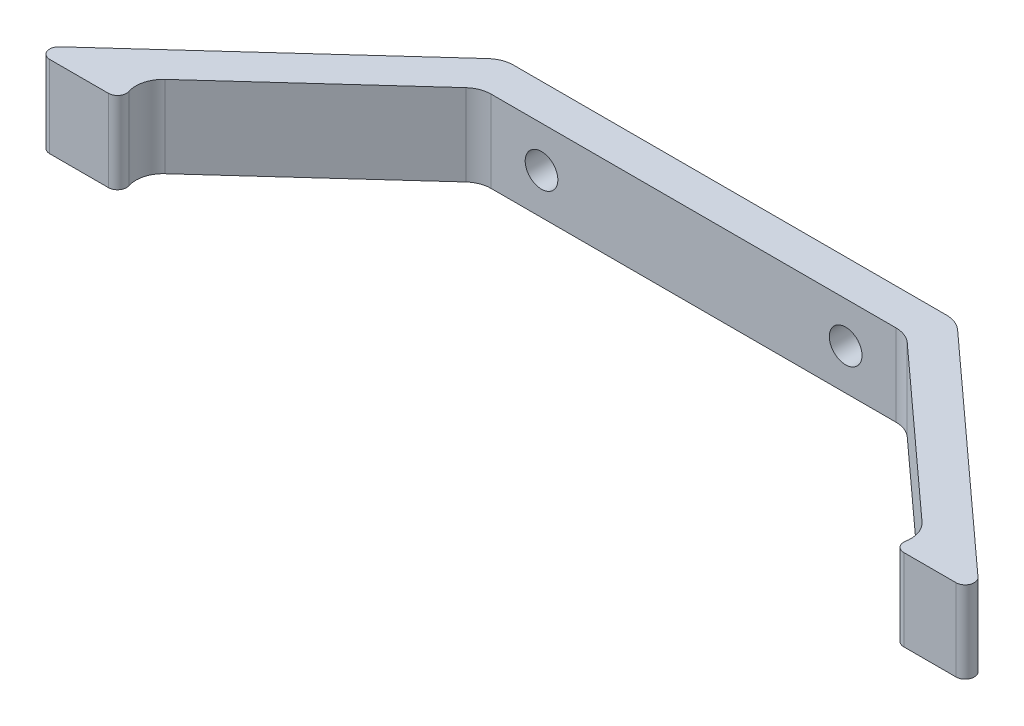
SolidWorks part; units mm, degrees
ref_plane "Front Plane" through (0, 0, 0) normal (0, 0, 1) x (1, 0, 0)
ref_plane "Top Plane" through (0, 0, 0) normal (0, 1, 0) x (1, 0, 0)
ref_plane "Right Plane" through (0, 0, 0) normal (1, 0, 0) x (0, 0, -1)
sketch "Sketch1" plane through (0, 0, 0) normal (0, 1, 0) x (1, 0, 0)
  line L0 (-25, 12.5) -> (-52.5, -12.5)
  line L1 (-52.5, -12.5) -> (-41.5, -12.5)
  line L2 (52.5, -12.5) -> (25, 12.5)
  line L3 (25, 12.5) -> (-25, 12.5)
  line L4 (-41.5, -12.5) -> (-43.502, -9.7258)
  line L5 (-43.502, -9.7258) -> (-23.4536, 8.5)
  line L6 (-23.4536, 8.5) -> (23.4536, 8.5)
  line L7 (23.4536, 8.5) -> (44.0714, -10.2435)
  line L8 (44.0714, -10.2435) -> (41.5, -12.5)
  line L9 (41.5, -12.5) -> (52.5, -12.5)
  point P5 (0, 12.5)
  point P7 (38.75, 0)
  dimension "D1" = 50
  dimension "D2" = 105
  dimension "D3" = 25
  dimension "D4" = 4
  dimension "D5" = 4
  dimension "D6" = 4
  dimension "D7" = 11
extrude "Boss-Extrude1" add sketch "Sketch1" along normal blind 9
fillet "Fillet4" radius 1 4 edges at (-41.5, 4.5, 12.5) (-52.5, 4.5, 12.5) (52.5, 4.5, 12.5) (41.5, 4.5, 12.5)
fillet "Fillet5" radius 3 6 edges at (44.0714, 4.5, 10.2435) (25, 4.5, -12.5) (23.4536, 4.5, -8.5) (-23.4536, 4.5, -8.5) (-25, 4.5, -12.5) (-43.502, 4.5, 9.7258)
hole_wizard "M3 Clearance Hole1" positions "Sketch3" profile "Sketch2" hole size "M3" standard "ANSI Metric" end condition through all
sketch "Sketch3" plane through (0, 0, -8.5) normal (0, 0, 1) x (1, 0, 0)
  line L1 (-22.2938, 9) -> (-22.2938, 0) construction
  line L2 (0, 0) -> (0, 14.3209) construction
  point P0 (-16.75, 4.5)
  point P8 (-22.2938, 4.5)
  point P15 (16.75, 4.5)
  dimension "D1" = 16.75
sketch "Sketch2" plane through (-16.75, 4.5, -8.5) normal (1, 0, 0) x (0, -1, 0)
  line L0 (0, 0) -> (0, 4)
  line L1 (0, 4) -> (1.8, 4)
  line L2 (1.8, 4) -> (1.8, 0)
  line L5 (1.8, 0) -> (0, 0)
  line L11 (0, -6.35) -> (0, 107.95) construction
  dimension "Thru Hole Dia." = 3.6
  dimension "Thru Hole Depth" = 4
